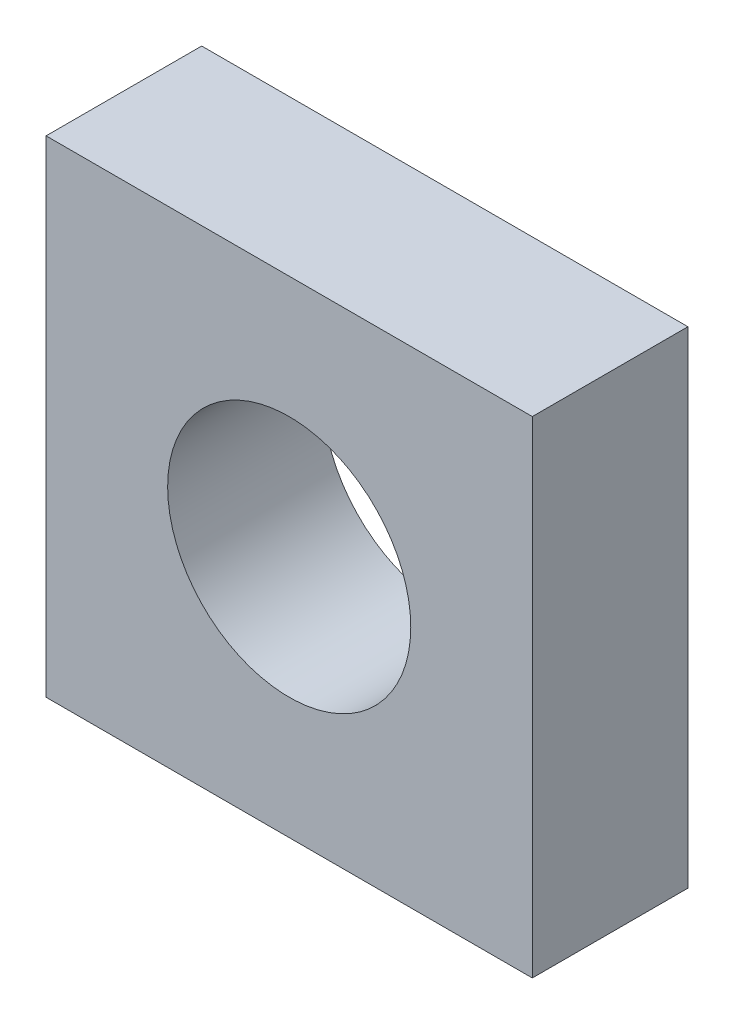
SolidWorks part; units mm, degrees
ref_plane "前视基准面" through (0, 0, 0) normal (0, 0, 1) x (1, 0, 0)
ref_plane "上视基准面" through (0, 0, 0) normal (0, 1, 0) x (1, 0, 0)
ref_plane "右视基准面" through (0, 0, 0) normal (1, 0, 0) x (0, 0, -1)
sketch "草图1" plane through (0, 0, 0) normal (0, 0, 1) x (1, 0, 0)
  line L1 (-2.5, -2.5) -> (2.5, -2.5)
  line L2 (-2.5, -2.5) -> (-2.5, 2.5)
  line L3 (-2.5, 2.5) -> (2.5, 2.5)
  line L4 (2.5, -2.5) -> (2.5, 2.5)
  line L5 (-2.5, -2.5) -> (2.5, 2.5) construction
  line L6 (-2.5, 2.5) -> (2.5, -2.5) construction
  point P0 (0, 0)
  dimension "D1" = 2.5
extrude "DIN562薄方螺母_外形" add sketch "草图1" along normal blind 1.6
sketch "草图2" plane through (0, 0, 0) normal (0, 0, 1) x (1, 0, 0)
  circle A0 centre (0, 0) radius 1.25
  dimension "D1" = 2.5
extrude "螺纹公称孔_简化无牙型" cut sketch "草图2" along normal blind 1.6
